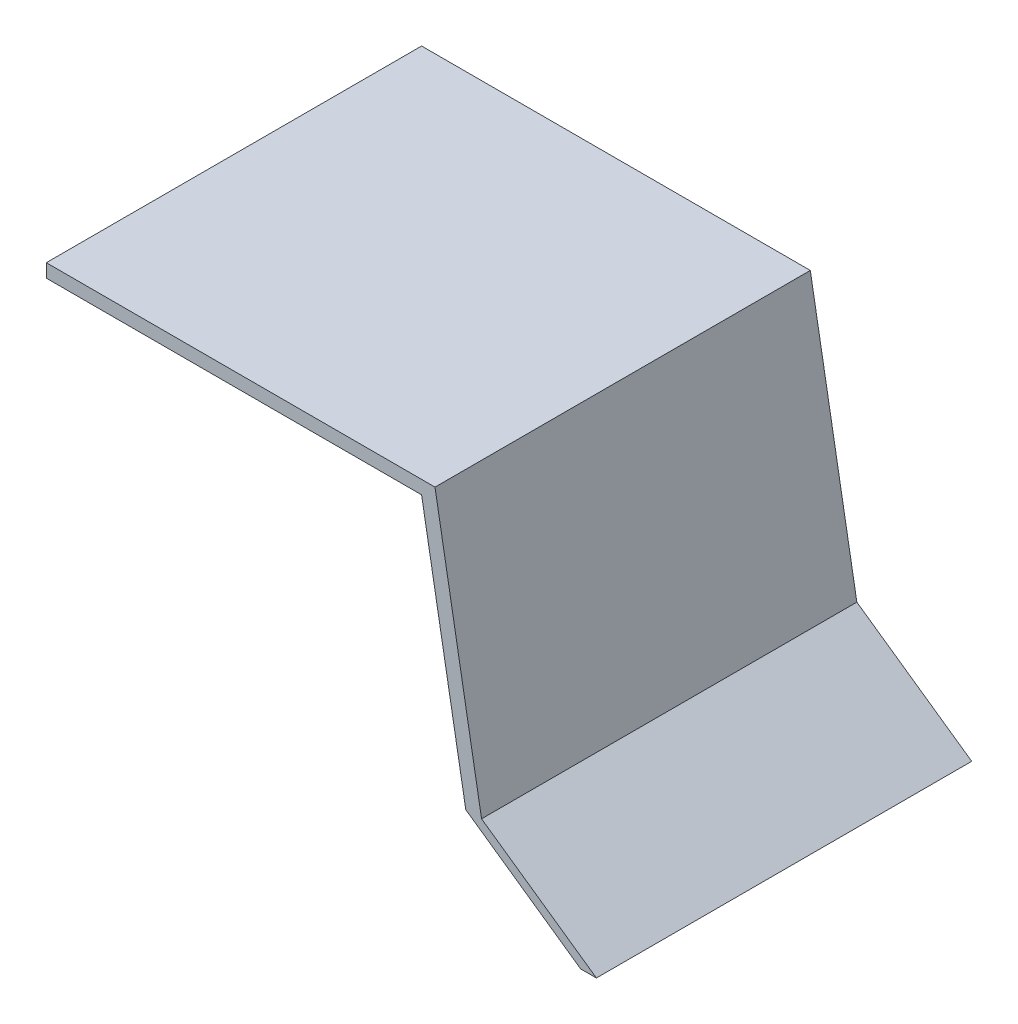
SolidWorks part; units mm, degrees
ref_plane "Front Plane" through (0, 0, 0) normal (0, 0, 1) x (1, 0, 0)
ref_plane "Top Plane" through (0, 0, 0) normal (0, 1, 0) x (1, 0, 0)
ref_plane "Right Plane" through (0, 0, 0) normal (1, 0, 0) x (0, 0, -1)
sketch "Sketch1" plane through (0, 0, 0) normal (0, 1, 0) x (1, 0, 0)
  line L1 (0, 0) -> (355.6, 0)
  line L2 (0, 0) -> (0, 355.6)
  line L3 (0, 355.6) -> (355.6, 355.6)
  line L4 (355.6, 0) -> (355.6, 355.6)
  dimension "D1" = 355.6
  dimension "D2" = 355.6
extrude "Boss-Extrude1" add sketch "Sketch1" along normal blind 12.7 contours L2 L3 L4 L1
ref_plane "Plane1" through (177.8, 0, 0) normal (1, 0, 0) x (0, 0, -1)
sketch "Sketch3" plane through (177.8, 0, 0) normal (1, 0, 0) x (0, 0, -1)
  line L0 (158.75, 0) -> (158.75, -15)
  line L1 (0, 0) -> (355.6, 0) construction
  line L4 (196.85, -15) -> (196.85, 0)
  line L5 (196.85, 0) -> (184.15, 0)
  line L6 (184.15, 0) -> (184.15, -15)
  line L8 (158.75, 0) -> (171.45, 0)
  line L9 (171.45, 0) -> (171.45, -15)
  line L10 (177.8, 0) -> (177.8, -34.05) construction
  arc A0 (158.75, -15) -> (196.85, -15) centre (177.8, -15) ccw
  arc A3 (184.15, -15) -> (171.45, -15) centre (177.8, -15) cw
  point P6 (177.8, -34.05)
  point P16 (177.8, -21.35)
  point P19 (177.8, 0)
  dimension "D3" = 15
  dimension "D4" = 12.7
  dimension "D1" = 6.35
  dimension "D2" = 12.7
extrude "Boss-Extrude2" add sketch "Sketch3" along normal mid plane 25.4
sketch "Sketch6" plane through (0, 0, 0) normal (0, 0, 1) x (1, 0, 0)
  line L0 (368.3, 12.7) -> (412.4066, -237.4412)
  line L2 (397.4673, -237.4412) -> (355.6, 0)
  line L4 (0, 0) -> (355.6, 0) construction
  line L5 (355.6, 0) -> (355.6, 12.7)
  line L6 (355.6, 12.7) -> (368.3, 12.7)
  line L7 (412.4066, -237.4412) -> (521.2315, -313.6412)
  line L8 (521.2315, -313.6412) -> (506.2922, -313.6412)
  line L9 (506.2922, -313.6412) -> (397.4673, -237.4412)
  dimension "D1" = 254
  dimension "D2" = 100
  dimension "D3" = 12.7
  dimension "D4" = 35
  dimension "D5" = 76.2
extrude "Boss-Extrude4" add sketch "Sketch6" against normal up to surface (355.6 mm away) up to face at (177.8, 6.35, -355.6)
